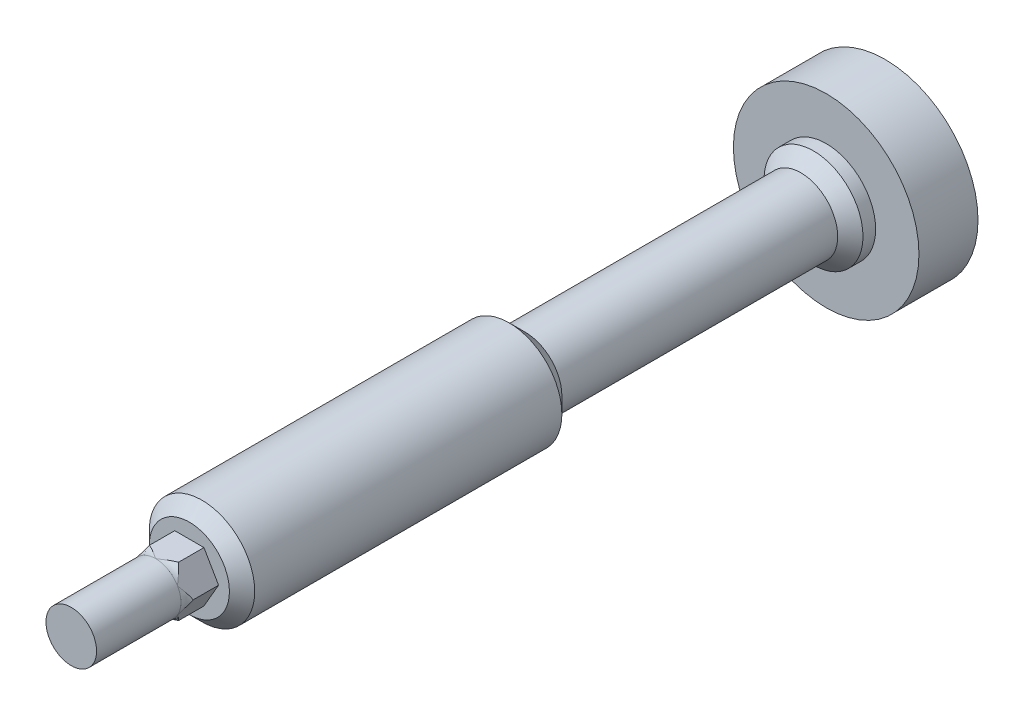
SolidWorks part; units mm, degrees
ref_plane "Front" through (0, 0, 0) normal (0, 0, 1) x (1, 0, 0)
ref_plane "Top" through (0, 0, 0) normal (0, 1, 0) x (1, 0, 0)
ref_plane "Right" through (0, 0, 0) normal (1, 0, 0) x (0, 0, -1)
sketch "Sketch1" plane through (0, 0, 0) normal (0, 1, 0) x (1, 0, 0)
  line L0 (0, 0) -> (0, 82.5)
  line L1 (0, 82.5) -> (11, 82.5)
  line L2 (11, 82.5) -> (11, 75.5)
  line L3 (11, 75.5) -> (5.865, 75.5)
  line L4 (5.865, 75.5) -> (5.865, 74)
  line L5 (5.865, 74) -> (4.365, 72.5)
  line L6 (4.365, 72.5) -> (4.365, 39.8)
  line L7 (4.365, 39.8) -> (6.25, 37.915)
  line L8 (6.25, 37.915) -> (6.25, 1.5)
  line L9 (6.25, 1.5) -> (4.75, 0)
  line L10 (4.75, 0) -> (0, 0)
  point P3 (0, 0)
  point P13 (4.365, 39.36)
  dimension "D1" = 82.5
  dimension "D2" = 11
  dimension "D3" = 7
  dimension "D4" = 1.5
  dimension "D5" = 4.365
  dimension "D6" = 45
  dimension "D7" = 1.5
  dimension "D8" = 6.25
  dimension "D9" = 1.5
  dimension "D10" = 39.8
revolve "Revolve1" add sketch "Sketch1" angle 360 about L0
sketch "Sketch2" plane through (0, 0, 0) normal (0, 0, 1) x (1, 0, 0)
  line L1 (3.4641, 0) -> (1.7321, 3)
  line L2 (1.7321, 3) -> (-1.7321, 3)
  line L3 (-1.7321, 3) -> (-3.4641, 0)
  line L4 (-3.4641, 0) -> (-1.7321, -3)
  line L5 (-1.7321, -3) -> (1.7321, -3)
  line L6 (1.7321, -3) -> (3.4641, 0)
  circle A0 centre (0, 0) radius 3 construction
  dimension "D1" = 6
extrude "Boss-Extrude1" add sketch "Sketch2" along normal blind 14
sketch "Sketch3" plane through (0, 0, 14) normal (0, 0, 1) x (1, 0, 0)
  circle A0 centre (0, 0) radius 3
extrude "Cut-Extrude1" cut sketch "Sketch3" against normal blind 10 flip side to cut
sketch "Sketch4" plane through (0, 0, 0) normal (0, 1, 0) x (1, 0, 0)
  line L0 (3.4641, -4) -> (3.4641, 0) construction
  line L1 (3.4641, -4) -> (2.5981, -4) construction
  line L2 (3, -14) -> (3, -4) construction
  line L3 (3.4641, -3) -> (3.4641, -4)
  line L4 (3.4641, -4) -> (3, -4)
  arc A0 (3, -4) -> (3.4641, -3) centre (4.3094, -4) cw
  dimension "D1" = 1
revolve "Cut-Revolve1" cut sketch "Sketch4" angle 360 about axis through (0, 0, 0) along (0, 0, 1)
